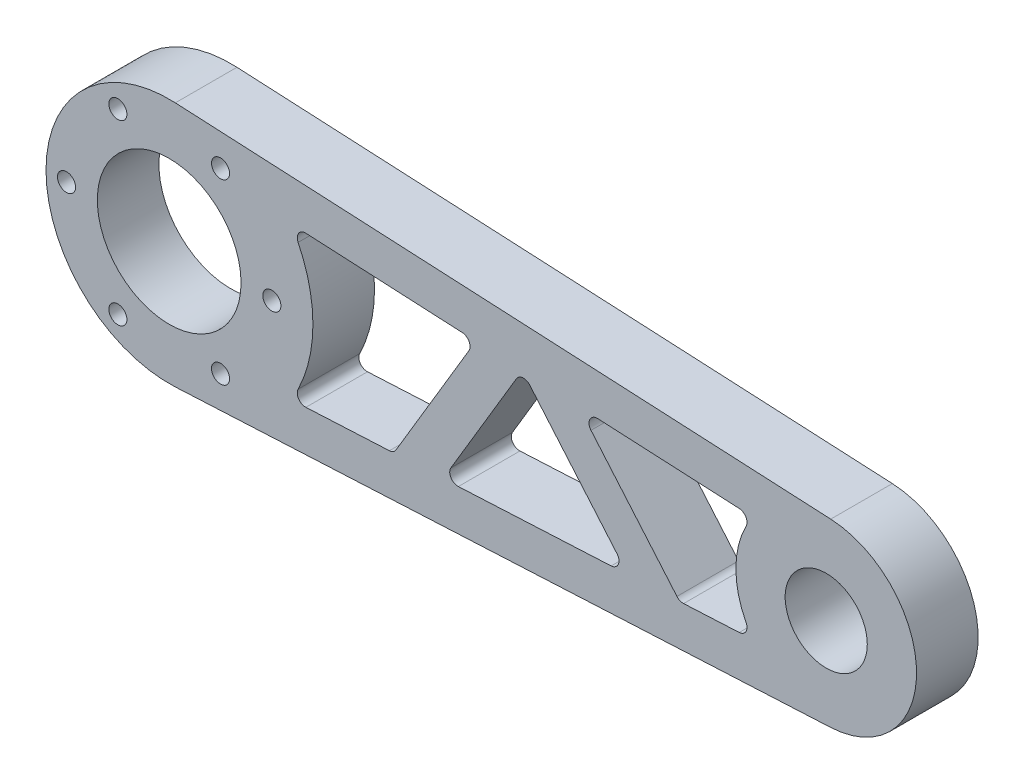
SolidWorks part; units mm, degrees
material "环氧树脂FR-4"
ref_plane "前视基准面" through (0, 0, 0) normal (0, 0, 1) x (1, 0, 0)
ref_plane "上视基准面" through (0, 0, 0) normal (0, 1, 0) x (1, 0, 0)
ref_plane "右视基准面" through (0, 0, 0) normal (1, 0, 0) x (0, 0, -1)
sketch "草图1" plane through (0, 0, 0) normal (0, 0, 1) x (1, 0, 0)
  line L0 (0, 0) -> (160, 0) construction
  line L3 (1.5, 29.9625) -> (161.1, 21.9725)
  line L4 (1.5, -29.9625) -> (161.1, -21.9725)
  arc A2 (161.1, -21.9725) -> (161.1, 21.9725) centre (160, 0) ccw
  arc A3 (1.5, 29.9625) -> (1.5, -29.9625) centre (0, 0) ccw
  dimension "D1" = 60
  dimension "D3" = 44
  dimension "D2" = 160
extrude "凸台-拉伸1" add sketch "草图1" along normal blind 15
sketch "草图2" plane through (0, 0, 15) normal (0, 0, 1) x (1, 0, 0)
  circle A0 centre (0, 0) radius 25 construction
  circle A2 centre (-25, 0) radius 2.2
  circle A3 centre (-12.5, 21.6506) radius 2.2
  circle A4 centre (12.5, 21.6506) radius 2.2
  circle A5 centre (25, 0) radius 2.2
  circle A6 centre (12.5, -21.6506) radius 2.2
  circle A7 centre (-12.5, -21.6506) radius 2.2
  circle A8 centre (160, 0) radius 10
  dimension "D1" = 50
  dimension "D2" = 4.4
  dimension "D4" = 20
  dimension "D3" = 6
extrude "切除-拉伸1" cut sketch "草图2" against normal through all
sketch "草图3" plane through (0, 0, 15) normal (0, 0, 1) x (1, 0, 0)
  line L0 (29.6869, 18.5388) -> (74.6869, 16.286)
  line L1 (74.6869, 16.286) -> (54.6869, -17.2873)
  line L2 (54.6869, -17.2873) -> (29.6869, -18.5388)
  line L3 (161.1, 21.9725) -> (1.5, 29.9625) construction
  line L4 (1.5, -29.9625) -> (161.1, -21.9725) construction
  line L5 (85.9897, 15.7202) -> (66.6846, -16.6866)
  line L6 (66.6846, -16.6866) -> (111.6846, -14.4338)
  line L7 (111.6846, -14.4338) -> (85.9897, 15.7202)
  line L8 (99.7133, 15.0331) -> (142.184, 12.9069)
  line L9 (99.7133, 15.0331) -> (124.2852, -13.803)
  line L10 (124.2852, -13.803) -> (142.184, -12.9069)
  circle A0 centre (0, 0) radius 17.5
  arc A1 (29.6869, -18.5388) -> (29.6869, 18.5388) centre (0, 0) ccw
  arc A2 (142.184, 12.9069) -> (142.184, -12.9069) centre (160, 0) ccw
  dimension "D1" = 35
  dimension "D2" = 70
  dimension "D10" = 44
  dimension "D3" = 10
  dimension "D4" = 10
  dimension "D5" = 25
  dimension "D6" = 45
  dimension "D7" = 10
  dimension "D8" = 10
  dimension "D9" = 10
  dimension "D11" = 10
  dimension "D12" = 10
  dimension "D13" = 10
  dimension "D14" = 45
extrude "切除-拉伸2" cut sketch "草图3" against normal through all
fillet "圆角1" radius 2 11 edges at (142.184, 12.9069, 7.5) (142.184, -12.9069, 7.5) (124.2852, -13.803, 7.5) (99.7133, 15.0331, 7.5) (111.6846, -14.4338, 7.5) (85.9897, 15.7202, 7.5) (66.6846, -16.6866, 7.5) (29.6869, -18.5388, 7.5) (54.6869, -17.2873, 7.5) (74.6869, 16.286, 7.5) (29.6869, 18.5388, 7.5)
